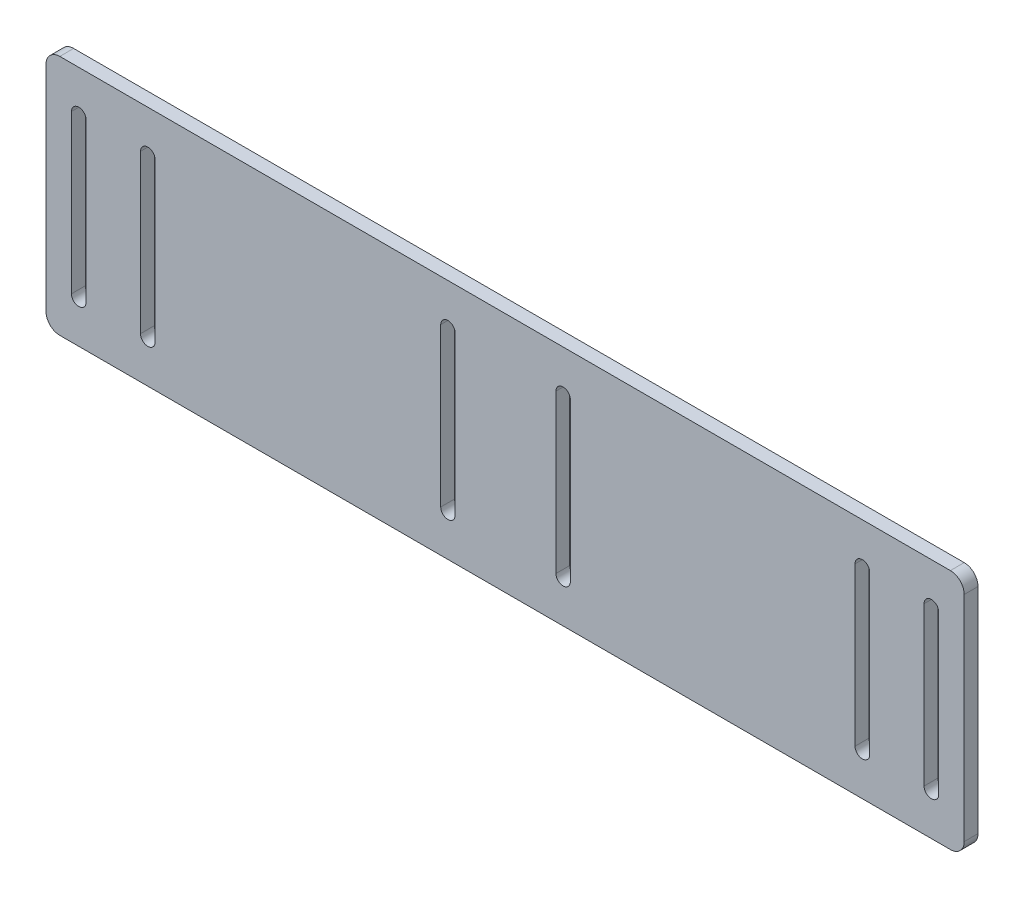
SolidWorks part; units mm, degrees
ref_plane "Front Plane" through (0, 0, 0) normal (0, 0, 1) x (1, 0, 0)
ref_plane "Top Plane" through (0, 0, 0) normal (0, 1, 0) x (1, 0, 0)
ref_plane "Right Plane" through (0, 0, 0) normal (1, 0, 0) x (0, 0, -1)
sketch "Sketch2" plane through (0, 0, -1552.3847) normal (0, 0, 1) x (1, 0, 0)
  line L0 (-0.1188, 700) -> (-0.1188, 560) construction
  line L1 (-493.1188, 700) -> (-493.1188, 560)
  line L3 (-440.1188, 700) -> (-440.1188, 560) construction
  line L6 (-480.1188, 700) -> (-479.9788, 560) construction
  line L7 (38.8812, 700) -> (38.8812, 560) construction
  line L8 (-480.1188, 700) -> (-493.1188, 700)
  line L9 (-480.1188, 700) -> (38.8812, 700)
  line L10 (-480.1188, 700) -> (-480.1188, 560) construction
  line L11 (-480.1188, 560) -> (38.8812, 560)
  line L12 (38.8812, 700) -> (38.8812, 560)
  line L13 (-480.1188, 560) -> (-493.1188, 560)
  line L14 (-493.1188, 713) -> (-493.1188, 547) construction
  line L15 (-427.1188, 584.25) -> (-427.1188, 675.75) construction
  line L16 (-431.3688, 584.25) -> (-431.3688, 675.75) construction
  line L17 (-422.8688, 584.25) -> (-422.8688, 675.75) construction
  line L18 (15.6312, 700) -> (15.6312, 560) construction
  line L19 (24.1312, 700) -> (24.1312, 560) construction
  line L20 (-467.1188, 584.25) -> (-467.1188, 675.75) construction
  line L21 (-20.1188, 700) -> (-20.1188, 560) construction
  line L22 (-462.8688, 584.25) -> (-462.8688, 675.75) construction
  line L25 (-471.3688, 584.25) -> (-471.3688, 675.75) construction
  line L28 (-220.6188, 700) -> (-220.6188, 560) construction
  line L29 (-24.3688, 700) -> (-24.3688, 560) construction
  line L30 (-15.8688, 700) -> (-15.8688, 560) construction
  line L31 (24.1312, 700) -> (15.6312, 700)
  line L32 (19.8812, 700) -> (19.8812, 560) construction
  line L33 (19.8812, 584.25) -> (19.8812, 675.75) construction
  line L34 (15.6312, 584.25) -> (15.6312, 675.75)
  line L35 (24.1312, 584.25) -> (24.1312, 675.75)
  line L36 (-434.1188, 584.25) -> (-434.1188, 675.75) construction
  line L37 (19.8812, 580) -> (19.8812, 560) construction
  line L38 (-20.1188, 584.25) -> (-20.1188, 675.75) construction
  line L39 (-15.8688, 584.25) -> (-15.8688, 675.75)
  line L40 (-24.3688, 584.25) -> (-24.3688, 675.75)
  line L41 (-421.1188, 584.25) -> (-421.1188, 675.75) construction
  line L42 (-425.3688, 584.25) -> (-425.3688, 675.75) construction
  line L43 (-416.8688, 584.25) -> (-416.8688, 675.75) construction
  line L44 (-461.1188, 584.25) -> (-461.1188, 675.75) construction
  line L45 (-456.8688, 584.25) -> (-456.8688, 675.75) construction
  line L46 (-465.3688, 584.25) -> (-465.3688, 675.75) construction
  line L47 (-493.1188, 713) -> (51.8812, 713) construction
  line L48 (-493.1188, 547) -> (51.8812, 547) construction
  line L49 (51.8812, 713) -> (51.8812, 547) construction
  line L50 (-438.3688, 584.25) -> (-438.3688, 675.75)
  line L51 (-429.8688, 584.25) -> (-429.8688, 675.75)
  line L52 (-474.1188, 584.25) -> (-474.1188, 675.75) construction
  line L53 (-469.8688, 584.25) -> (-469.8688, 675.75)
  line L54 (-478.3688, 584.25) -> (-478.3688, 675.75)
  arc A4 (15.6312, 584.25) -> (24.1312, 584.25) centre (19.8812, 584.25) ccw
  arc A5 (24.1312, 675.75) -> (15.6312, 675.75) centre (19.8812, 675.75) ccw
  arc A6 (-15.8688, 584.25) -> (-24.3688, 584.25) centre (-20.1188, 584.25) cw
  arc A7 (-24.3688, 675.75) -> (-15.8688, 675.75) centre (-20.1188, 675.75) cw
  arc A8 (-425.3688, 584.25) -> (-416.8688, 584.25) centre (-421.1188, 584.25) ccw construction
  arc A9 (-416.8688, 675.75) -> (-425.3688, 675.75) centre (-421.1188, 675.75) ccw construction
  arc A10 (-456.8688, 584.25) -> (-465.3688, 584.25) centre (-461.1188, 584.25) cw construction
  arc A11 (-465.3688, 675.75) -> (-456.8688, 675.75) centre (-461.1188, 675.75) cw construction
  arc A12 (-431.3688, 584.25) -> (-422.8688, 584.25) centre (-427.1188, 584.25) ccw construction
  arc A13 (-422.8688, 675.75) -> (-431.3688, 675.75) centre (-427.1188, 675.75) ccw construction
  arc A14 (-462.8688, 584.25) -> (-471.3688, 584.25) centre (-467.1188, 584.25) cw construction
  arc A15 (-471.3688, 675.75) -> (-462.8688, 675.75) centre (-467.1188, 675.75) cw construction
  arc A16 (-438.3688, 584.25) -> (-429.8688, 584.25) centre (-434.1188, 584.25) ccw
  arc A17 (-429.8688, 675.75) -> (-438.3688, 675.75) centre (-434.1188, 675.75) ccw
  arc A18 (-469.8688, 584.25) -> (-478.3688, 584.25) centre (-474.1188, 584.25) cw
  arc A19 (-478.3688, 675.75) -> (-469.8688, 675.75) centre (-474.1188, 675.75) cw
  point P18 (-427.1188, 630)
  point P34 (19.8812, 700)
  point P39 (-20.1188, 675.25)
  point P40 (-20.1188, 574.75)
  point P41 (-20.1188, 574.75)
  point P42 (-20.1188, 560)
  point P43 (19.8812, 630)
  point P44 (-20.1188, 560)
  point P49 (19.8812, 680)
  point P50 (19.8812, 580)
  point P57 (-20.1188, 630)
  point P64 (-421.1188, 630)
  point P71 (-461.1188, 630)
  point P77 (-467.1188, 630)
  point P83 (-434.1188, 630)
  point P90 (-474.1188, 630)
  line M5 (-14.8688, 700) -> (-14.8688, -300)
  line M7 (14.6312, -300) -> (14.6312, 700)
  line M8 (14.6312, 700) -> (-14.8688, 700)
  dimension "D3" = 20
  dimension "D1" = 8.5
  dimension "D2" = 100
  dimension "D4" = 8.5
  dimension "D5" = 140
  dimension "D6" = 20
  dimension "D7" = 13
  dimension "D8" = 2
  dimension "D9" = 2
extrude "Boss-Extrude3" add sketch "Sketch2" along normal blind 8 contours L10 L11 L9 A9 L43 A8 L42 L40 A7 L39 A6 L46 A11 L45 A10 M5 | L11 M5 M7 M8 | L12 L9 L11 A5 L35 A4 L34 M7
fillet "Fillet1" radius 8 4 edges at (38.8812, 700, -1548.3847) (38.8812, 560, -1548.3847) (-493.1188, 560, -1548.3847) (-493.1188, 700, -1548.3847)
sketch "Sketch5" [suppressed] plane through (0, 0, -532.7708) normal (0, 0, 1) x (1, 0, 0)
  line L1 (-230.6188, 619.9) -> (-210.5188, 619.9)
  line L2 (-230.6188, 619.9) -> (-230.6188, 640)
  line L3 (-230.6188, 640) -> (-210.5188, 640)
  line L4 (-210.5188, 619.9) -> (-210.5188, 640)
  dimension "D1" = 20.1
  dimension "D2" = 20.1
extrude "Cut-Extrude1" [suppressed] cut sketch "Sketch5" against normal blind 2.5
sketch "Sketch6" [suppressed] plane through (0, 0, -560.7601) normal (0, 0, 1) x (1, 0, 0)
  line L0 (-191.0988, 632.575) -> (-202.5522, 632.575) construction
  line L1 (-202.5522, 627.425) -> (-191.0988, 627.425) construction
  line L2 (-250.1388, 627.425) -> (-238.6855, 627.425) construction
  line L3 (-238.6855, 632.575) -> (-250.1388, 632.575) construction
  line L4 (-191.0988, 632.575) -> (-202.5522, 632.575)
  line L5 (-202.5522, 627.425) -> (-191.0988, 627.425)
  line L6 (-250.1388, 627.425) -> (-238.6855, 627.425)
  line L7 (-238.6855, 632.575) -> (-250.1388, 632.575)
  arc A0 (-191.0988, 627.425) -> (-191.0988, 632.575) centre (-191.0988, 630) ccw construction
  arc A1 (-202.5522, 632.575) -> (-202.5522, 627.425) centre (-202.5522, 630) ccw construction
  arc A2 (-238.6855, 627.425) -> (-238.6855, 632.575) centre (-238.6855, 630) ccw construction
  arc A3 (-250.1388, 632.575) -> (-250.1388, 627.425) centre (-250.1388, 630) ccw construction
  arc A4 (-191.0988, 627.425) -> (-191.0988, 632.575) centre (-191.0988, 630) ccw
  arc A5 (-202.5522, 632.575) -> (-202.5522, 627.425) centre (-202.5522, 630) ccw
  arc A6 (-238.6855, 627.425) -> (-238.6855, 632.575) centre (-238.6855, 630) ccw
  arc A7 (-250.1388, 632.575) -> (-250.1388, 627.425) centre (-250.1388, 630) ccw
extrude "Cut-Extrude2" [suppressed] cut sketch "Sketch6" against normal blind 10
sketch "Sketch7" plane through (0, 0, -1544.3847) normal (0, 0, 1) x (1, 0, 0)
  line L0 (-415.1188, 680) -> (-190.3286, 680) construction
  line L1 (-415.1188, 580) -> (-184.7009, 580) construction
  line L2 (-419.3688, 675.75) -> (-190.3286, 675.75) construction
  line L3 (-419.3688, 584.25) -> (-184.7009, 584.25) construction
  line L4 (-244.8188, 617) -> (-244.8188, 644.2) construction
  line L5 (-244.8188, 617) -> (-244.8188, 644.2) construction
  line L6 (-187.2438, 675.75) -> (-187.2438, 584.25) construction
  line L7 (-253.9938, 700) -> (-253.9938, 560) construction
  line L8 (-191.4188, 675.75) -> (-191.4188, 584.25) construction
  line L9 (-183.0688, 675.75) -> (-183.0688, 584.25) construction
  line L10 (-260.2438, 675.75) -> (-260.2438, 584.25) construction
  line L11 (-256.0688, 675.75) -> (-256.0688, 584.25)
  line L12 (-485.1188, 560) -> (30.8812, 560) construction
  line L13 (-485.1188, 700) -> (30.8812, 700) construction
  line L14 (-485.1188, 560) -> (30.8812, 560) construction
  line L15 (-485.1188, 700) -> (30.8812, 700) construction
  line L16 (-247.8188, 617) -> (-247.8188, 644.2) construction
  line L17 (-223.6188, 630) -> (-223.6188, 711.2377) construction
  line L18 (-256.9938, 675.75) -> (-256.9938, 584.25) construction
  line L19 (-220.6188, 630) -> (-220.6188, 711.2377) construction
  line L20 (-253.9938, 675.75) -> (-253.9938, 584.25) construction
  line L21 (-249.8188, 675.75) -> (-249.8188, 584.25) construction
  line L22 (-258.1688, 675.75) -> (-258.1688, 584.25) construction
  line L23 (-252.8188, 675.75) -> (-252.8188, 584.25) construction
  line L24 (-261.1688, 675.75) -> (-261.1688, 584.25) construction
  line L25 (-190.2438, 675.75) -> (-190.2438, 584.25) construction
  line L26 (-194.4188, 675.75) -> (-194.4188, 584.25) construction
  line L27 (-186.0688, 675.75) -> (-186.0688, 584.25) construction
  line L28 (-264.4188, 675.75) -> (-264.4188, 584.25)
  line L29 (-193.4938, 675.75) -> (-193.4938, 584.25) construction
  line L30 (-197.6688, 675.75) -> (-197.6688, 584.25)
  line L31 (-189.3188, 675.75) -> (-189.3188, 584.25)
  line L32 (-226.8688, 630) -> (-226.8688, 711.2377) construction
  arc A0 (-410.8688, 675.75) -> (-419.3688, 675.75) centre (-415.1188, 675.75) ccw construction
  arc A1 (-419.3688, 584.25) -> (-410.8688, 584.25) centre (-415.1188, 584.25) ccw construction
  arc A2 (-249.8188, 675.75) -> (-258.1688, 675.75) centre (-253.9938, 675.75) ccw construction
  arc A3 (-258.1688, 584.25) -> (-249.8188, 584.25) centre (-253.9938, 584.25) ccw construction
  arc A4 (-191.4188, 675.75) -> (-183.0688, 675.75) centre (-187.2438, 675.75) cw construction
  arc A5 (-183.0688, 584.25) -> (-191.4188, 584.25) centre (-187.2438, 584.25) cw construction
  arc A6 (-252.8188, 675.75) -> (-261.1688, 675.75) centre (-256.9938, 675.75) ccw construction
  arc A7 (-261.1688, 584.25) -> (-252.8188, 584.25) centre (-256.9938, 584.25) ccw construction
  arc A8 (-194.4188, 675.75) -> (-186.0688, 675.75) centre (-190.2438, 675.75) cw construction
  arc A9 (-186.0688, 584.25) -> (-194.4188, 584.25) centre (-190.2438, 584.25) cw construction
  arc A10 (-256.0688, 675.75) -> (-264.4188, 675.75) centre (-260.2438, 675.75) ccw
  arc A11 (-264.4188, 584.25) -> (-256.0688, 584.25) centre (-260.2438, 584.25) ccw
  arc A12 (-197.6688, 675.75) -> (-189.3188, 675.75) centre (-193.4938, 675.75) cw
  arc A13 (-189.3188, 584.25) -> (-197.6688, 584.25) centre (-193.4938, 584.25) cw
  point P8 (-187.2438, 630)
  point P36 (-253.9938, 675.75)
  point P37 (-253.9938, 584.25)
  point P40 (-253.9938, 630)
  point P47 (-193.4938, 630)
  point P53 (-190.2438, 630)
  point P60 (-256.9938, 675.75)
  point P61 (-256.9938, 584.25)
  point P64 (-256.9938, 630)
  point P74 (-260.2438, 630)
  dimension "D2" = 2
  dimension "D3" = 2
  dimension "D4" = 8.35
  dimension "D1" = 5
  dimension "D6" = 3.25
  dimension "D5" = 2
extrude "Cut-Extrude3" cut sketch "Sketch7" against normal blind 10
equation "\"2.5.00mm\"=10"
